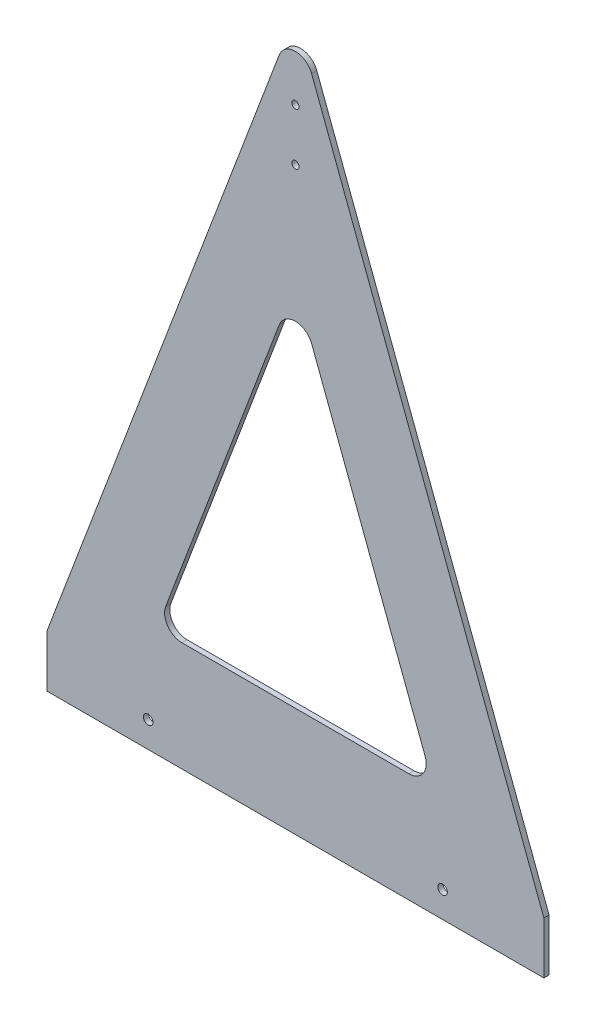
SolidWorks part; units mm, degrees
ref_plane "Alzado" through (0, 0, 0) normal (0, 0, 1) x (1, 0, 0)
ref_plane "Planta" through (0, 0, 0) normal (0, 1, 0) x (1, 0, 0)
ref_plane "Vista lateral" through (0, 0, 0) normal (1, 0, 0) x (0, 0, -1)
sketch "Croquis1" plane through (0, 0, 0) normal (0, 0, 1) x (1, 0, 0)
  line L0 (0, -2892.9169) -> (0, 141752.9275) construction
  line L1 (-143.5, 0) -> (143.5, 0)
  line L2 (143.5, 0) -> (143.5, 30)
  line L3 (143.5, 30) -> (9.3552, 385.2267)
  line L4 (-143.5, 30) -> (-9.3552, 385.2267)
  line L5 (-143.5, 0) -> (-143.5, 30)
  line L7 (-10, 375) -> (10, 375) construction
  line L8 (-10, 375) -> (-10, 355) construction
  line L9 (-10, 355) -> (10, 355) construction
  line L10 (10, 375) -> (10, 355) construction
  line L11 (-10, 375) -> (10, 355) construction
  line L12 (-10, 355) -> (10, 375) construction
  line L13 (-10, 345) -> (10, 345) construction
  line L14 (-10, 345) -> (-10, 325) construction
  line L15 (-10, 325) -> (10, 325) construction
  line L16 (10, 345) -> (10, 325) construction
  line L17 (-10, 345) -> (10, 325) construction
  line L18 (-10, 325) -> (10, 345) construction
  circle A0 centre (0, 365) radius 2.1
  circle A1 centre (0, 335) radius 2.1
  arc A2 (9.3552, 385.2267) -> (-9.3552, 385.2267) centre (0, 381.6939) ccw
  point P1 (0, 365)
  point P9 (0, 0)
  point P14 (0, 335)
  point P25 (0, 410)
  dimension "D10" = 4.2
  dimension "D11" = 4.2
  dimension "D12" = 10
  dimension "D1" = 143.5
  dimension "D2" = 30
  dimension "D3" = 410
  dimension "D4" = 20
  dimension "D5" = 20
  dimension "D6" = 375
  dimension "D7" = 20
  dimension "D8" = 20
  dimension "D9" = 345
extrude "Saliente-Extruir1" add sketch "Croquis1" along normal blind 3
hole_wizard "Taladro de margen para M51" positions "Croquis2" profile "Croquis3" hole size "M5" standard "ISO" end condition through all
sketch "Croquis2" plane through (0, 0, 0) normal (0, 0, -1) x (-1, 0, 0)
  point P0 (-85, 15)
  point P2 (85, 15)
  dimension "D1" = 170
  dimension "D2" = 85
  dimension "D3" = 15
sketch "Croquis3" plane through (85, 15, 0) normal (1, 0, 0) x (0, 1, 0)
  line L0 (0, 0) -> (0, 3)
  line L1 (0, 3) -> (2.75, 3)
  line L2 (2.75, 3) -> (2.75, 0)
  line L5 (2.75, 0) -> (0, 0)
  line L11 (0, -6.35) -> (0, 107.95) construction
  dimension "Diámetro de taladro hasta el siguiente" = 5.5
  dimension "Profundidad de taladro hasta el siguiente" = 3
sketch "Croquis4" plane through (0, 0, 0) normal (0, 0, -1) x (-1, 0, 0)
  line L0 (0, -1000) -> (0, 49000) construction
  line L1 (9.3552, 250.2267) -> (74.8896, 76.6861)
  line L2 (65.5344, 63.1533) -> (-65.5344, 63.1533)
  line L3 (9.3552, 385.2267) -> (143.5, 30) construction
  line L4 (143.5, 0) -> (-143.5, 0) construction
  line L5 (-9.3552, 250.2267) -> (-74.8896, 76.6861)
  arc A0 (74.8896, 76.6861) -> (65.5344, 63.1533) centre (65.5344, 73.1533) cw
  arc A1 (-74.8896, 76.6861) -> (-65.5344, 63.1533) centre (-65.5344, 73.1533) ccw
  arc A2 (9.3552, 250.2267) -> (-9.3552, 250.2267) centre (0, 246.6939) ccw
  point P11 (0, 63.1533)
  point P13 (80, 63.1533)
  point P16 (-80, 63.1533)
  point P19 (0, 275)
  dimension "D3" = 10
  dimension "D1" = 80
  dimension "D2" = 275
extrude "Cortar-Extruir1" cut sketch "Croquis4" against normal blind 3
